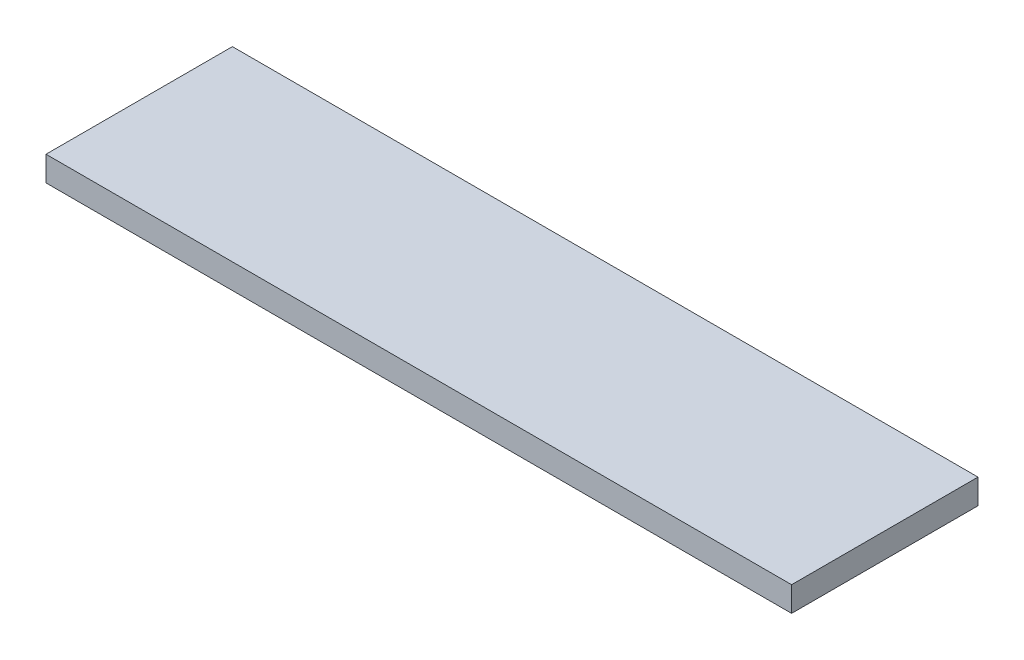
SolidWorks part; units mm, degrees
ref_plane "Front Plane" through (0, 0, 0) normal (0, 0, 1) x (1, 0, 0)
ref_plane "Top Plane" through (0, 0, 0) normal (0, 1, 0) x (1, 0, 0)
ref_plane "Right Plane" through (0, 0, 0) normal (1, 0, 0) x (0, 0, -1)
sketch "Sketch1" plane through (0, 0, 0) normal (0, 1, 0) x (1, 0, 0)
  line L1 (-30, -7.5) -> (30, -7.5)
  line L2 (-30, -7.5) -> (-30, 7.5)
  line L3 (-30, 7.5) -> (30, 7.5)
  line L4 (30, -7.5) -> (30, 7.5)
  line L5 (-30, -7.5) -> (30, 7.5) construction
  line L6 (-30, 7.5) -> (30, -7.5) construction
  point P0 (0, 0)
  dimension "D1" = 60
  dimension "D2" = 15
extrude "Boss-Extrude1" add sketch "Sketch1" along normal blind 2
